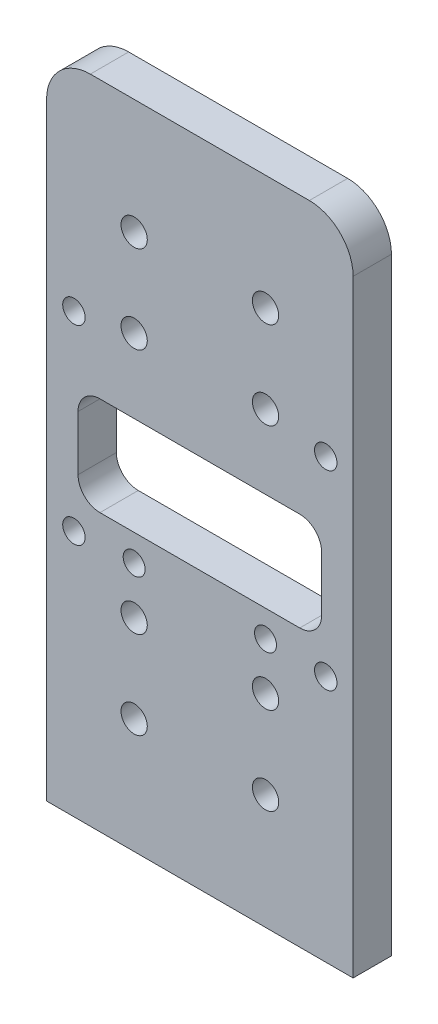
SolidWorks part; units mm, degrees
ref_plane "Plan de face" through (0, 0, 0) normal (0, 0, 1) x (1, 0, 0)
ref_plane "Plan de dessus" through (0, 0, 0) normal (0, 1, 0) x (1, 0, 0)
ref_plane "Plan de droite" through (0, 0, 0) normal (1, 0, 0) x (0, 0, -1)
sketch "Esquisse1" plane through (0, 0, 0) normal (0, 0, 1) x (1, 0, 0)
  line L1 (0, 0) -> (28, 0)
  line L2 (0, 0) -> (0, 55.5)
  line L3 (4, 59.5) -> (24, 59.5)
  line L4 (28, 0) -> (28, 55.5)
  arc A2 (24, 59.5) -> (28, 55.5) centre (24, 55.5) cw
  arc A3 (0, 55.5) -> (4, 59.5) centre (4, 55.5) cw
  point P0 (28, 0.3362)
  point P9 (0, 0)
  point P12 (28, 59.5)
  point P15 (0, 59.5)
  point P17 (0, 0)
  dimension "D1" = 28
  dimension "D2" = 59.5
extrude "Boss.-Extru.1" add sketch "Esquisse1" along normal blind 3.5
sketch "Esquisse2" plane through (0, 0, 3.5) normal (0, 0, 1) x (1, 0, 0)
  line L0 (-3.9361, 18.5) -> (39.5369, 18.5) construction
  line L1 (14, -3.4341) -> (14, 66.5491) construction
  line L2 (0, 55.5) -> (0, 0) construction
  line L3 (0, 0) -> (28, 0) construction
  line L4 (8, -3.4341) -> (8, 61.0958) construction
  line L5 (20, 62.5518) -> (20, -2.6727) construction
  line L6 (-1.9394, 10.5) -> (40.0153, 10.5) construction
  line L7 (-3.9361, 49) -> (38.5954, 49) construction
  line L8 (-10.2317, 41) -> (41.5104, 41) construction
  line L9 (24, 59.5) -> (4, 59.5) construction
  line L10 (-2.7315, 40) -> (31.2638, 40) construction
  line L11 (-6.2586, 22.6) -> (34.9171, 22.6) construction
  line L12 (2.5, 73.0678) -> (2.5, -26.9316) construction
  line L13 (25.5, 66.5491) -> (25.5, -18.2006) construction
  circle A0 centre (8, 10.5) radius 1.2
  circle A1 centre (20, 10.5) radius 1.2
  circle A2 centre (8, 18.5) radius 1.2
  circle A3 centre (20, 18.5) radius 1.2
  circle A4 centre (8, 49) radius 1.2
  circle A5 centre (8, 41) radius 1.2
  circle A6 centre (20, 49) radius 1.2
  circle A7 centre (20, 41) radius 1.2
  circle A8 centre (2.5, 40) radius 1.025
  circle A9 centre (2.5, 22.6) radius 1.025
  circle A10 centre (25.5, 40) radius 1.025
  circle A11 centre (25.5, 22.6) radius 1.025
  dimension "D2" = 18.5
  dimension "D5" = 2.4
  dimension "D6" = 2.4
  dimension "D7" = 2.4
  dimension "D8" = 2.4
  dimension "D12" = 2.4
  dimension "D13" = 2.4
  dimension "D14" = 2.4
  dimension "D15" = 2.4
  dimension "D20" = 2.05
  dimension "D21" = 2.05
  dimension "D22" = 2.05
  dimension "D23" = 2.05
  dimension "D1" = 14
  dimension "D3" = 6
  dimension "D4" = 12
  dimension "D9" = 8
  dimension "D10" = 10.5
  dimension "D11" = 8
  dimension "D16" = 19.5
  dimension "D17" = 18.4
  dimension "D18" = 11.5
  dimension "D19" = 23
extrude "Enlèv. mat.-Extru.1" cut sketch "Esquisse2" against normal through all
sketch "Esquisse3" plane through (0, 0, 3.5) normal (0, 0, 1) x (1, 0, 0)
  line L0 (24, 59.5) -> (4, 59.5) construction
  line L1 (4.875, 34.25) -> (23.125, 34.25)
  line L2 (2.875, 32.25) -> (2.875, 27.25)
  line L3 (4.875, 25.25) -> (23.125, 25.25)
  line L4 (25.125, 32.25) -> (25.125, 27.25)
  line L5 (0, 0) -> (28, 0) construction
  line L6 (14, 63.5119) -> (14, -29.6665) construction
  line L7 (28, 0) -> (28, 55.5) construction
  arc A0 (25.125, 32.25) -> (23.125, 34.25) centre (23.125, 32.25) ccw
  arc A1 (25.125, 27.25) -> (23.125, 25.25) centre (23.125, 27.25) cw
  arc A2 (2.875, 27.25) -> (4.875, 25.25) centre (4.875, 27.25) ccw
  arc A3 (4.875, 34.25) -> (2.875, 32.25) centre (4.875, 32.25) ccw
  point P12 (14, 34.25)
  point P17 (25.125, 25.25)
  point P20 (2.875, 25.25)
  dimension "D5" = 2
  dimension "D1" = 25.25
  dimension "D2" = 25.25
  dimension "D3" = 22.25
  dimension "D4" = 14
extrude "Enlèv. mat.-Extru.2" cut sketch "Esquisse3" against normal through all
sketch "Esquisse7" plane through (0, 0, 3.5) normal (0, 0, 1) x (1, 0, 0)
  line L0 (4.875, 25.25) -> (23.125, 25.25) construction
  line L1 (0, 55.5) -> (0, 0) construction
  circle A0 centre (8, 22.82) radius 1
  circle A1 centre (20, 22.82) radius 1
  dimension "D1" = 2
  dimension "D2" = 2
  dimension "D3" = 12
  dimension "D4" = 2.43
  dimension "D5" = 8
extrude "Enlèv. mat.-Extru.4" cut sketch "Esquisse7" against normal through all
